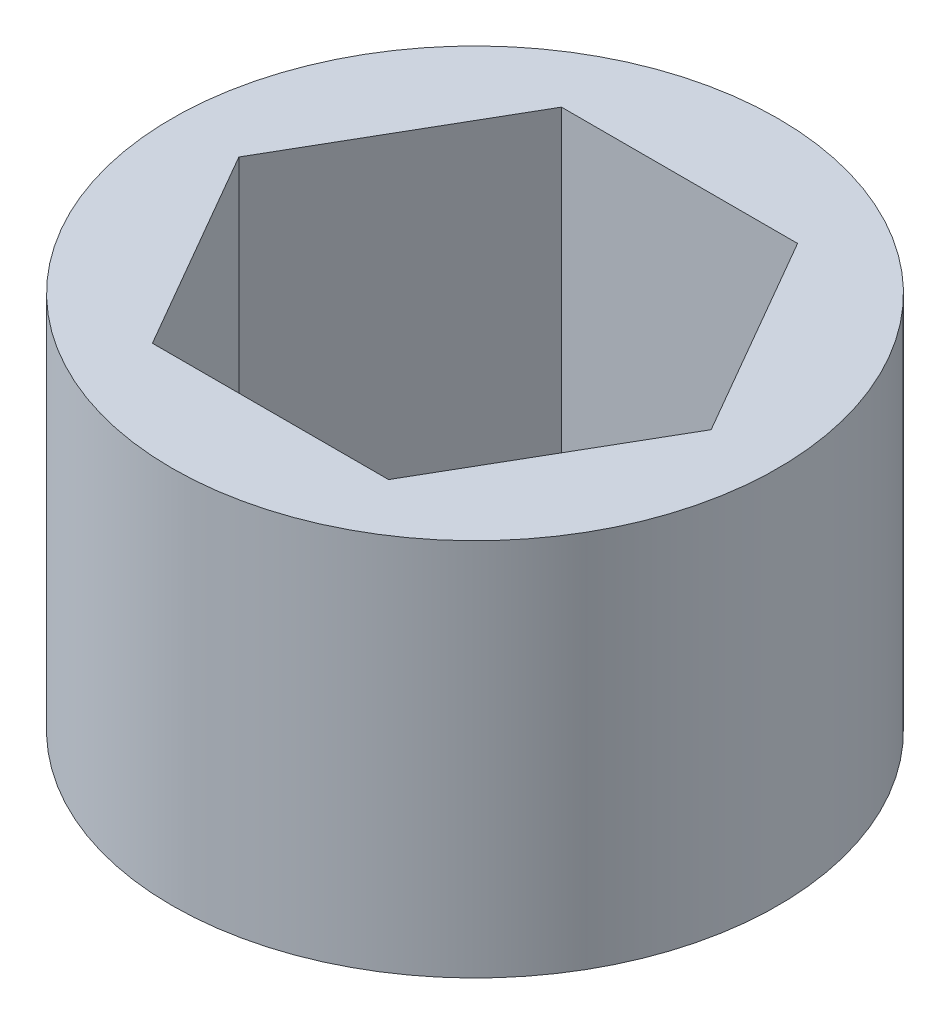
SolidWorks part; units mm, degrees
ref_plane "Front Plane" through (0, 0, 0) normal (0, 0, 1) x (1, 0, 0)
ref_plane "Top Plane" through (0, 0, 0) normal (0, 1, 0) x (1, 0, 0)
ref_plane "Right Plane" through (0, 0, 0) normal (1, 0, 0) x (0, 0, -1)
sketch "Sketch1" plane through (0, 0, 0) normal (0, 1, 0) x (1, 0, 0)
  line L1 (7.9189, 0) -> (3.9595, 6.858)
  line L2 (3.9595, 6.858) -> (-3.9595, 6.858)
  line L3 (-3.9595, 6.858) -> (-7.9189, 0)
  line L4 (-7.9189, 0) -> (-3.9595, -6.858)
  line L5 (-3.9595, -6.858) -> (3.9595, -6.858)
  line L6 (3.9595, -6.858) -> (7.9189, 0)
  circle A0 centre (0, 0) radius 6.858 construction
  circle A1 centre (0, 0) radius 10.16
  dimension "D2" = 20.32
  dimension "D1" = 13.716
extrude "Boss-Extrude1" add sketch "Sketch1" along normal blind 12.7
